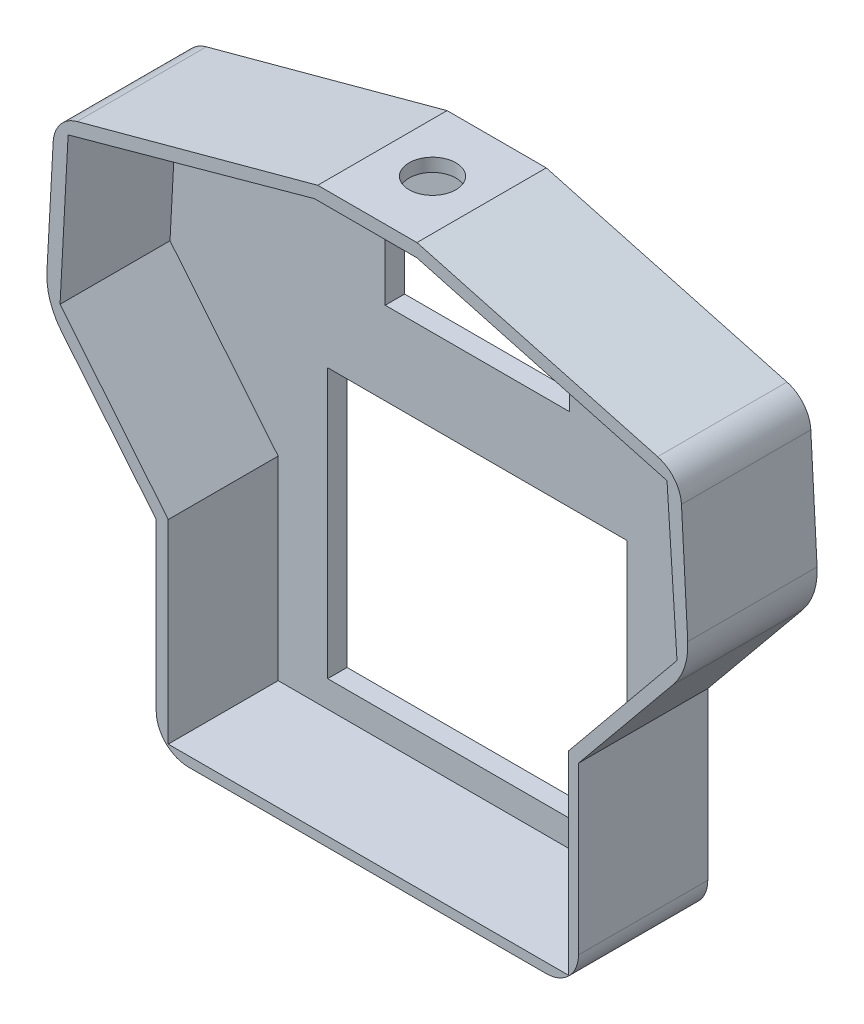
SolidWorks part; units mm, degrees
ref_plane "Front Plane" through (0, 0, 0) normal (0, 0, 1) x (1, 0, 0)
ref_plane "Top Plane" through (0, 0, 0) normal (0, 1, 0) x (1, 0, 0)
ref_plane "Right Plane" through (0, 0, 0) normal (1, 0, 0) x (0, 0, -1)
sketch "Sketch1" plane through (0, 0, 0) normal (0, 0, 1) x (1, 0, 0)
  line L1 (-15.34, 87.9098) -> (15.34, 87.9098)
  line L2 (-65.2932, -26.5499) -> (-65.2932, -87.9098)
  line L3 (-65.2932, -87.9098) -> (65.2932, -87.9098)
  line L15 (0, 87.9098) -> (-15.34, 87.9098) construction
  line L18 (15.34, 87.9098) -> (96.7598, 65.8832)
  line L19 (96.7598, 65.8832) -> (99.5131, 15.1433)
  line L20 (99.5131, 15.1433) -> (65.2932, -26.5499)
  line L21 (65.2932, -26.5499) -> (65.2932, -87.9098)
  line L22 (-99.5131, 15.1433) -> (-65.2932, -26.5499)
  line L23 (-96.7598, 65.8832) -> (-99.5131, 15.1433)
  line L24 (-15.34, 87.9098) -> (-96.7598, 65.8832)
  point P0 (0, 0)
extrude "Boss-Extrude1" add sketch "Sketch1" along normal blind 40
sketch "Sketch3" plane through (0, 0, 40) normal (0, 0, 1) x (1, 0, 0)
  line L0 (-92.5348, 62.8169) -> (-16.3715, 83.8152)
  line L1 (-16.3715, 83.8152) -> (15.3038, 83.8152)
  line L2 (-92.5348, 62.8169) -> (-95.0261, 16.1936)
  line L3 (-95.0261, 16.1936) -> (-61.5712, -24.7353)
  line L4 (-61.5712, -24.7353) -> (-61.5712, -84.8829)
  line L5 (-61.5712, -84.8829) -> (60.1476, -84.8829)
  line L6 (15.3038, 83.8152) -> (92.6738, 62.8169)
  line L7 (92.6738, 62.8169) -> (95.7706, 16.1936)
  line L8 (95.7706, 16.1936) -> (62.2688, -24.7353)
  line L9 (62.2688, -24.7353) -> (62.2688, -84.8829)
  line L10 (62.2688, -84.8829) -> (60.1476, -84.8829)
extrude "Cut-Extrude1" cut sketch "Sketch3" against normal blind 34 and the other way blind 2
sketch "Sketch4" plane through (0, 0, 6) normal (0, 0, 1) x (1, 0, 0)
  line L1 (-28.4722, 57.1224) -> (28.4722, 57.1224)
  line L2 (-28.4722, 57.1224) -> (-28.4722, 32.2092)
  line L3 (-28.4722, 32.2092) -> (28.4722, 32.2092)
  line L4 (28.4722, 57.1224) -> (28.4722, 32.2092)
  line L5 (-28.4722, 57.1224) -> (28.4722, 32.2092) construction
  line L6 (-28.4722, 32.2092) -> (28.4722, 57.1224) construction
  line L7 (-46.2674, -76.6971) -> (46.2674, -76.6971)
  line L8 (-46.2674, -76.6971) -> (-46.2674, 6.5842)
  line L9 (-46.2674, 6.5842) -> (46.2674, 6.5842)
  line L10 (46.2674, -76.6971) -> (46.2674, 6.5842)
  line L11 (-46.2674, -76.6971) -> (46.2674, 6.5842) construction
  line L12 (-46.2674, 6.5842) -> (46.2674, -76.6971) construction
  point P0 (0, 44.6658)
  point P5 (0, -35.0564)
sketch "Sketch5" plane through (0, 87.9098, 0) normal (0, 1, 0) x (1, 0, 0)
  circle A0 centre (0, -19.8443) radius 7.241
extrude "Cut-Extrude2" cut sketch "Sketch5" against normal blind 19
extrude "Cut-Extrude3" cut sketch "Sketch4" against normal blind 19
fillet "Fillet1" radius 10 1 edges at (96.7598, 65.8832, 20)
fillet "Fillet2" radius 10 1 edges at (-96.7598, 65.8832, 20)
fillet "Fillet5" radius 20 1 edges at (-99.5131, 15.1433, 20)
fillet "Fillet6" radius 20 1 edges at (99.5131, 15.1433, 20)
fillet "Fillet11" radius 10 1 edges at (65.2932, -87.9098, 20)
fillet "Fillet12" radius 10 1 edges at (-65.2932, -87.9098, 20)
